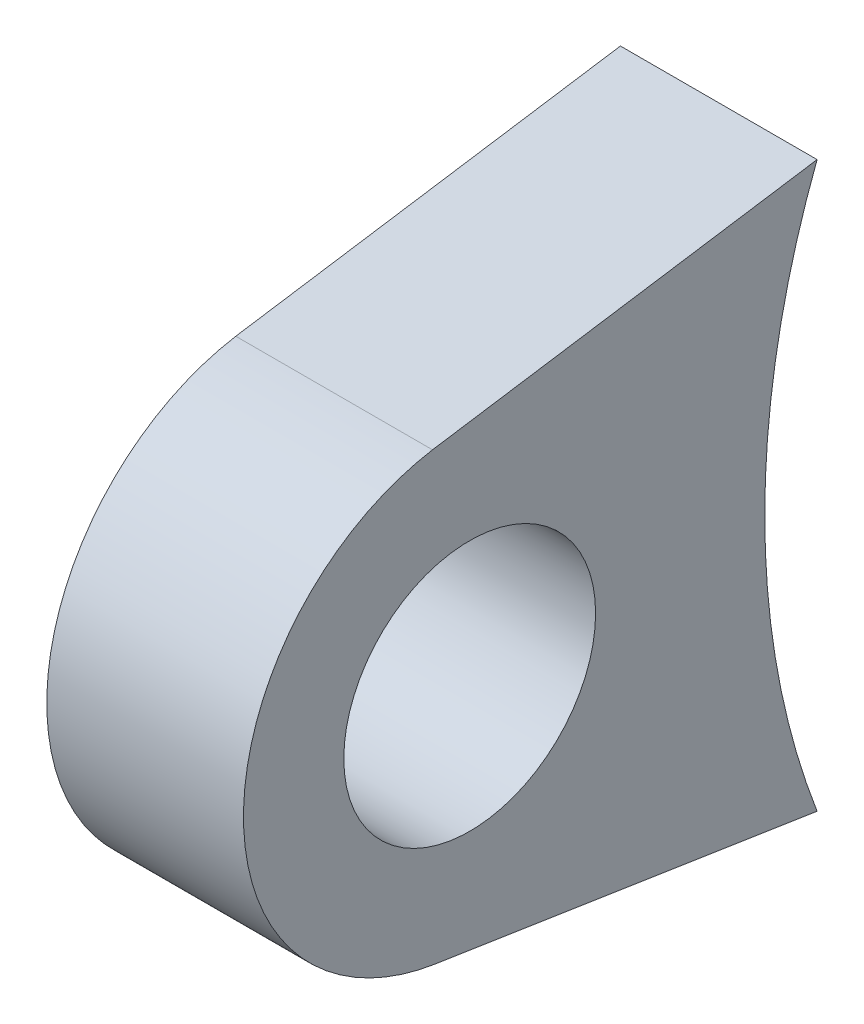
SolidWorks part; units mm, degrees
ref_plane "Płaszczyzna przednia" through (0, 0, 0) normal (0, 0, 1) x (1, 0, 0)
ref_plane "Płaszczyzna górna" through (0, 0, 0) normal (0, 1, 0) x (1, 0, 0)
ref_plane "Płaszczyzna prawa" through (0, 0, 0) normal (1, 0, 0) x (0, 0, -1)
sketch "Szkic19" plane through (91.7854, 0, 0) normal (1, 0, 0) x (0, 0, -1)
  line L0 (-27.5, 0) -> (0, 0)
  line L1 (-28.446, 5.6717) -> (-18.6696, 7.1726)
  line L2 (-18.6696, 7.1726) -> (-18.6696, -7.1726)
  line L3 (-18.6696, -7.1726) -> (-28.3723, -5.6835)
  circle A0 centre (0, 0) radius 20
  circle A1 centre (-27.5, 0) radius 3.2
  circle A2 centre (-27.5, 0) radius 5.75
  circle A3 centre (0, 0) radius 20 construction
  point P5 (-18.6696, -7.1726)
  dimension "D2" = 11.5
extrude "Dodanie-wyciągnięcie4" add sketch "Szkic19" against normal blind 5
